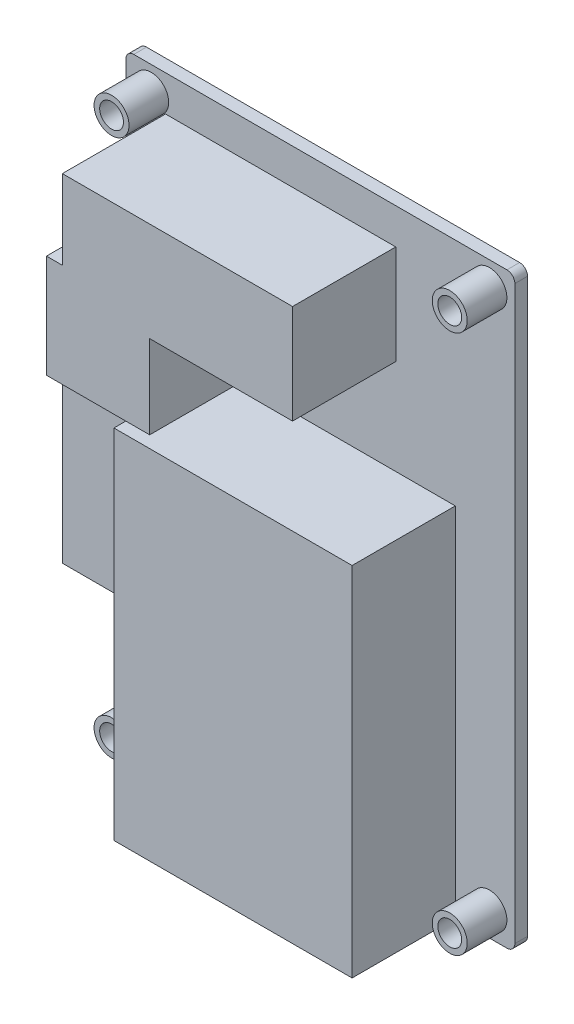
SolidWorks part; units mm, degrees
ref_plane "前视基准面" through (0, 0, 0) normal (0, 0, 1) x (1, 0, 0)
ref_plane "上视基准面" through (0, 0, 0) normal (0, 1, 0) x (1, 0, 0)
ref_plane "右视基准面" through (0, 0, 0) normal (1, 0, 0) x (0, 0, -1)
other "Configuration Table"
sketch "草图1" plane through (0, 0, 0) normal (0, 0, 1) x (1, 0, 0)
  line L0 (-19.1143, 0) -> (15.4601, 0) construction
  line L1 (0, 11.1032) -> (0, -14.8979) construction
  line L3 (-23.5, -37) -> (23.5, -37)
  line L4 (-24.5, -36) -> (-24.5, 36)
  line L5 (-23.5, 37) -> (23.5, 37)
  line L6 (24.5, -36) -> (24.5, 36)
  line L7 (-24.5, -37) -> (24.5, 37) construction
  line L8 (-24.5, 37) -> (24.5, -37) construction
  arc A0 (-23.5, -37) -> (-24.5, -36) centre (-23.5, -36) cw
  arc A1 (-24.5, 36) -> (-23.5, 37) centre (-23.5, 36) cw
  arc A2 (23.5, -37) -> (24.5, -36) centre (23.5, -36) ccw
  arc A3 (23.5, 37) -> (24.5, 36) centre (23.5, 36) cw
  point P4 (0, 0)
  dimension "D3" = 1
  dimension "D1" = 74
  dimension "D2" = 49
extrude "凸台-拉伸1" add sketch "草图1" along normal blind 1.6
sketch "草图2" plane through (0, 0, 1.6) normal (0, 0, 1) x (1, 0, 0)
  line L0 (-39.412, 0) -> (39.9569, 0) construction
  line L1 (21.3, -33.95) -> (-21.3, -33.95) construction
  line L2 (21.3, -33.95) -> (21.3, 33.95) construction
  line L3 (21.3, 33.95) -> (-21.3, 33.95) construction
  line L4 (-21.3, -33.95) -> (-21.3, 33.95) construction
  line L5 (0, 42.4996) -> (0, -69.2966) construction
  circle A0 centre (21.3, 33.95) radius 1.5
  circle A1 centre (-21.3, 33.95) radius 1.5
  circle A2 centre (-21.3, -33.95) radius 1.5
  circle A3 centre (21.3, -33.95) radius 1.5
  dimension "D3" = 3
  dimension "D1" = 42.6
  dimension "D2" = 67.9
extrude "切除-拉伸1" cut sketch "草图2" against normal through all
sketch "草图5" plane through (0, 0, 1.6) normal (0, 0, 1) x (1, 0, 0)
  circle A0 centre (-21.3, 33.95) radius 2.2
  circle A1 centre (-21.3, 33.95) radius 1.5 construction
  circle A2 centre (-21.3, 33.95) radius 1.5
  circle A3 centre (21.3, -33.95) radius 1.5 construction
  circle A4 centre (-21.3, -33.95) radius 1.5 construction
  circle A5 centre (21.3, 33.95) radius 1.5 construction
  circle A6 centre (21.3, -33.95) radius 1.5
  circle A7 centre (-21.3, -33.95) radius 1.5
  circle A8 centre (21.3, 33.95) radius 1.5
  circle A9 centre (21.3, -33.95) radius 2.2
  circle A10 centre (-21.3, -33.95) radius 2.2
  circle A11 centre (21.3, 33.95) radius 2.2
  dimension "D1" = 4.4
extrude "凸台-拉伸2" add sketch "草图5" along normal blind 5
sketch "草图6" plane through (0, 0, 1.6) normal (0, 0, 1) x (1, 0, 0)
  line L0 (-8.5, 9.5) -> (-21.5, 9.5)
  line L1 (-21.5, 9.5) -> (-21.5, 22.5)
  line L2 (-19.5, 32.5) -> (9.5, 32.5)
  line L3 (9.5, 32.5) -> (9.5, 20)
  line L4 (9.5, 20) -> (-8.5, 20)
  line L5 (-8.5, 20) -> (-8.5, 9.5)
  line L6 (23.5, 37) -> (-23.5, 37) construction
  line L7 (24.5, -36) -> (24.5, 36) construction
  line L8 (-24.5, 36) -> (-24.5, -36) construction
  line L9 (-21.5, 22.5) -> (-19.5, 22.5)
  line L10 (-19.5, 22.5) -> (-19.5, 32.5)
  line L11 (-13, 8) -> (17, 8)
  line L12 (-13, 8) -> (-13, -37)
  line L13 (-13, -37) -> (17, -37)
  line L14 (17, 8) -> (17, -37)
  line L15 (-23.5, -37) -> (23.5, -37) construction
  dimension "D1" = 12.5
  dimension "D2" = 18
  dimension "D3" = 23
  dimension "D4" = 4.5
  dimension "D5" = 15
  dimension "D6" = 3
  dimension "D7" = 2
  dimension "D8" = 13
  dimension "D9" = 45
  dimension "D10" = 7.5
  dimension "D11" = 30
extrude "凸台-拉伸3" add sketch "草图6" along normal blind 13
sketch "草图7" plane through (0, 0, 1.6) normal (0, 0, 1) x (1, 0, 0)
  line L0 (-24.5, 36) -> (-24.5, -36) construction
  line L1 (-24.5, -20) -> (-18.5, -20)
  line L3 (-24.5, 10) -> (-18.5, 10)
  line L4 (-18.5, -20) -> (-18.5, 10)
  line L5 (23.5, 37) -> (-23.5, 37) construction
  line L7 (-24.5, -20) -> (-29.5, -20)
  line L8 (-24.5, -20) -> (-24.5, 10)
  line L9 (-24.5, 10) -> (-29.5, 10)
  line L10 (-29.5, -20) -> (-29.5, 10)
  line M10 (-8.5, 9.5) -> (-21.5, 9.5)
  line M11 (-21.5, 9.5) -> (-21.5, 22.5)
  line M30 (-24.5, 36) -> (-24.5, -36)
  dimension "D1" = 6
  dimension "D2" = 30
  dimension "D3" = 27
  dimension "D4" = 5
extrude "凸台-拉伸4" add sketch "草图7" along normal blind 3 contours L10 L7 L9 M30 | L1 L4 L3 M10 M11 M30
